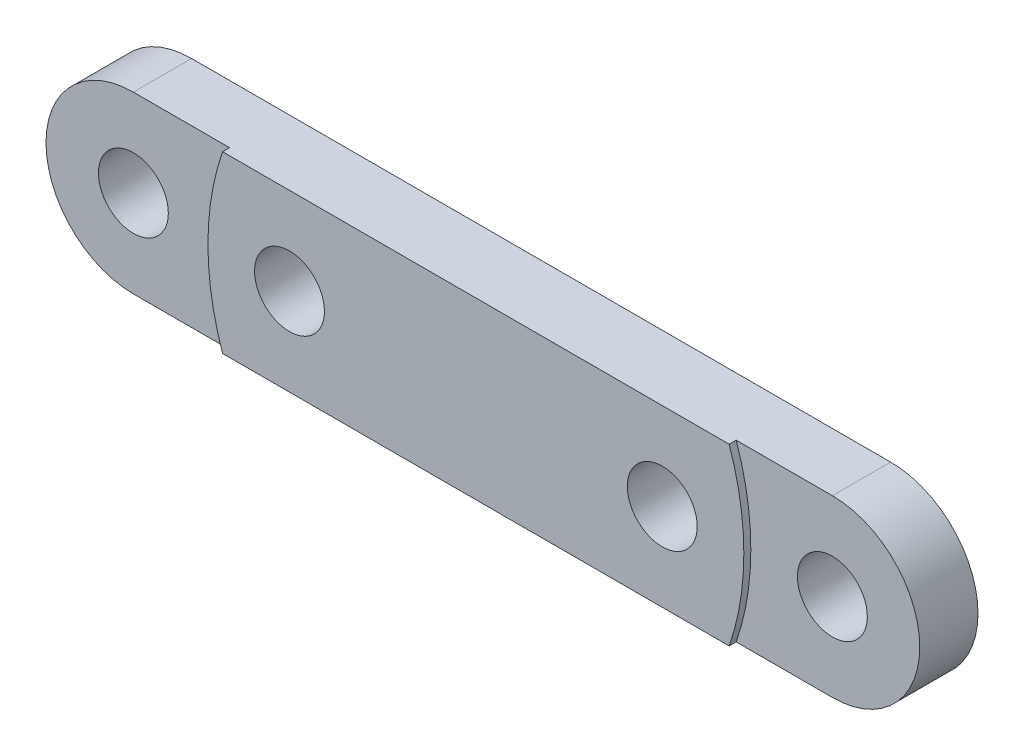
SolidWorks part; units mm, degrees
material "ABS"
ref_plane "Ebene vorne" through (0, 0, 0) normal (0, 0, 1) x (1, 0, 0)
ref_plane "Ebene oben" through (0, 0, 0) normal (0, 1, 0) x (1, 0, 0)
ref_plane "Ebene rechts" through (0, 0, 0) normal (1, 0, 0) x (0, 0, -1)
sketch "Skizze1" plane through (0, 0, 0) normal (0, 0, 1) x (1, 0, 0)
  line L0 (-15, 0) -> (15, 0) construction
  line L1 (-15, 3.75) -> (15, 3.75)
  line L2 (-15, -3.75) -> (15, -3.75)
  line L3 (0, 3.75) -> (0, -3.75) construction
  arc A0 (-15, 3.75) -> (-15, -3.75) centre (-15, 0) ccw
  arc A1 (15, -3.75) -> (15, 3.75) centre (15, 0) ccw
  circle A2 centre (-15, 0) radius 1.5
  circle A3 centre (15, 0) radius 1.5
  circle A4 centre (-8, 0) radius 1.5
  circle A5 centre (8, 0) radius 1.5
  point P2 (0, 0)
  dimension "D1" = 3
  dimension "D2" = 3
  dimension "D3" = 16
  dimension "D4" = 30
  dimension "D5" = 7.5
extrude "Base" add sketch "Skizze1" along normal blind 2.5
sketch "Skizze3" plane through (0, 0, 2.5) normal (0, 0, 1) x (1, 0, 0)
  line L0 (15, 3.75) -> (-15, 3.75) construction
  line L1 (10.8714, -3.75) -> (-10.8714, -3.75)
  line L2 (10.8714, -3.75) -> (10.8714, 3.75)
  line L3 (10.8714, 3.75) -> (-10.8714, 3.75)
  line L4 (-10.8714, -3.75) -> (-10.8714, 3.75)
  line L5 (10.8714, -3.75) -> (-10.8714, 3.75) construction
  line L6 (10.8714, 3.75) -> (-10.8714, -3.75) construction
  circle A0 centre (0, 0) radius 11.5
  circle A1 centre (-8, 0) radius 1.5
  circle A2 centre (8, 0) radius 1.5
  circle A3 centre (8, 0) radius 1.5 construction
  circle A4 centre (-8, 0) radius 1.5 construction
  circle M2 centre (-8, 0) radius 1.5
  line M5 (-15, -3.75) -> (15, -3.75)
  line M7 (15, 3.75) -> (-15, 3.75)
  circle M9 centre (8, 0) radius 1.5
  dimension "D1" = 23
extrude "Distancer" add sketch "Skizze3" along normal blind 0.3 contours L4 A0 | L2 A0 | L4 L2 M5 M7 M2 M9 | A1
